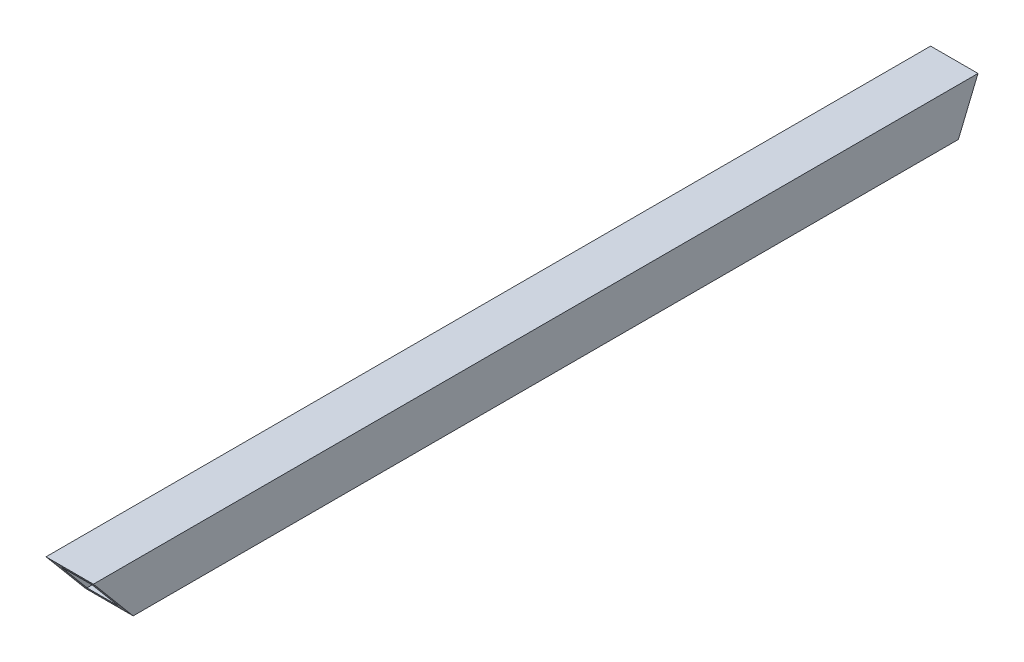
SolidWorks part; units mm, degrees
material "6061-T6 (SS)"
ref_plane "Front Plane" through (0, 0, 0) normal (0, 0, 1) x (1, 0, 0)
ref_plane "Top Plane" through (0, 0, 0) normal (0, 1, 0) x (1, 0, 0)
ref_plane "Right Plane" through (0, 0, 0) normal (1, 0, 0) x (0, 0, -1)
sketch "Sketch1" plane through (0, 0, 0) normal (0, 0, 1) x (1, 0, 0)
  line L1 (-9.525, -9.525) -> (9.525, -9.525)
  line L2 (-9.525, -9.525) -> (-9.525, 9.525)
  line L3 (-9.525, 9.525) -> (9.525, 9.525)
  line L4 (9.525, -9.525) -> (9.525, 9.525)
  line L5 (-9.525, -9.525) -> (9.525, 9.525) construction
  line L6 (-9.525, 9.525) -> (9.525, -9.525) construction
  line L7 (-6.35, -6.35) -> (6.35, -6.35)
  line L8 (-6.35, -6.35) -> (-6.35, 6.35)
  line L9 (-6.35, 6.35) -> (6.35, 6.35)
  line L10 (6.35, -6.35) -> (6.35, 6.35)
  line L11 (-6.35, -6.35) -> (6.35, 6.35) construction
  line L12 (-6.35, 6.35) -> (6.35, -6.35) construction
  point P0 (0, 0)
  point P5 (0, 0)
  dimension "D1" = 19.05
  dimension "D2" = 3.175
extrude "Boss-Extrude1" add sketch "Sketch1" along normal mid plane 355.6
sketch "Sketch2" plane through (9.525, 0, 0) normal (1, 0, 0) x (0, 0, -1)
  line L0 (-177.8, 9.525) -> (-161.8152, -9.525)
  line L1 (-177.8, -9.525) -> (177.8, -9.525) construction
  line L2 (-161.8152, -9.525) -> (-177.8, -9.525)
  line L3 (-177.8, -9.525) -> (-177.8, 9.525)
  line L4 (177.8, 9.525) -> (169.9092, -9.525)
  line L5 (169.9092, -9.525) -> (177.8, -9.525)
  line L6 (177.8, -9.525) -> (177.8, 9.525)
  dimension "D1" = 40
  dimension "D2" = 22.5
extrude "Cut-Extrude1" cut sketch "Sketch2" against normal through all
